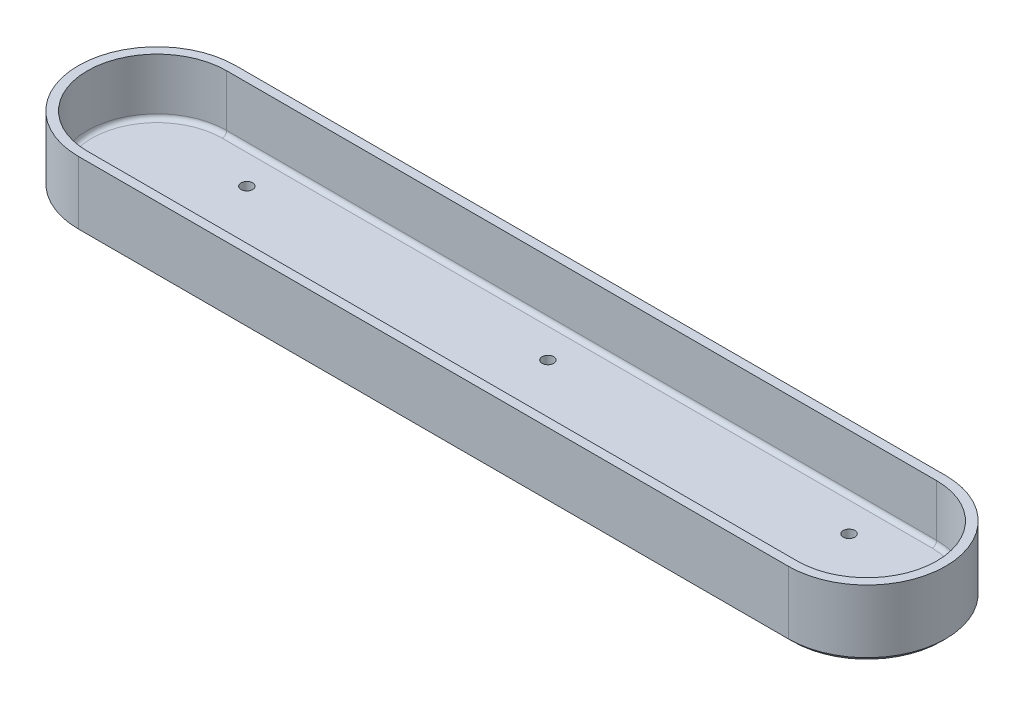
SolidWorks part; units mm, degrees
material "PLA"
ref_plane "Front Plane" through (0, 0, 0) normal (0, 0, 1) x (1, 0, 0)
ref_plane "Top Plane" through (0, 0, 0) normal (0, 1, 0) x (1, 0, 0)
ref_plane "Right Plane" through (0, 0, 0) normal (1, 0, 0) x (0, 0, -1)
sketch "Sketch1" plane through (0, 0, 0) normal (0, 1, 0) x (1, 0, 0)
  line L0 (-100.33, 0) -> (100.33, 0) construction
  line L1 (0, -55.9739) -> (0, 55.9739) construction
  line L2 (-100.33, 19.685) -> (100.33, 19.685)
  line L3 (-100.33, -19.685) -> (100.33, -19.685)
  arc A0 (-100.33, 19.685) -> (-100.33, -19.685) centre (-100.33, 0) ccw
  arc A1 (100.33, 19.685) -> (100.33, -19.685) centre (100.33, 0) cw
  circle A2 centre (-100.33, 0) radius 19.05 construction
  point P4 (0, 0)
  point P10 (0, 0)
  dimension "D2" = 0.635
  dimension "D3" = 38.1
  dimension "D1" = 200.66
extrude "MainBlock" add sketch "Sketch1" along normal blind 3.175
sketch "Sketch2" plane through (0, 0, 0) normal (0, -1, 0) x (1, 0, 0)
  line L0 (0, 0) -> (0, 50000) construction
  line L1 (-100.33, 22.225) -> (100.33, 22.225)
  line L2 (-100.33, -19.685) -> (100.33, -19.685)
  line L3 (100.33, 19.685) -> (-100.33, 19.685)
  line L5 (100.33, 19.685) -> (-100.33, 19.685)
  line L6 (-95.25, 0) -> (49904.75, 0) construction
  line L7 (100.33, -19.685) -> (-100.33, -19.685)
  line L8 (-100.33, -22.225) -> (100.33, -22.225)
  arc A0 (-100.33, 22.225) -> (-100.33, -22.225) centre (-100.33, 0) ccw
  arc A1 (100.33, 19.685) -> (100.33, -19.685) centre (100.33, 0) cw
  arc A2 (-100.33, 19.685) -> (-100.33, -19.685) centre (-100.33, 0) ccw
  arc A3 (100.33, -19.685) -> (100.33, 19.685) centre (100.33, 0) ccw
  arc A4 (-100.33, 19.685) -> (-100.33, -19.685) centre (-100.33, 0) ccw
  arc A6 (100.33, 22.225) -> (100.33, -22.225) centre (100.33, 0) cw
  point P0 (0, 19.685)
  point P15 (0, 22.225)
  point P16 (0, -19.685)
  point P19 (0, -22.225)
  dimension "D2" = 2.54
  dimension "2.1" = 44.45
  dimension "D1" = 0
extrude "Boss-Extrude1" add sketch "Sketch2" against normal blind 19.05
sketch "Sketch3" plane through (0, 0, 0) normal (0, -1, 0) x (1, 0, 0)
  line L0 (0, 0) -> (50000, 0) construction
  line L1 (0, 0) -> (0, 50000) construction
  line L2 (-100.33, 0.9216) -> (-100.33, 50000.9216) construction
  arc A0 (-100.33, 22.225) -> (-100.33, -22.225) centre (-100.33, 0) ccw construction
  arc A1 (-100.33, 22.225) -> (-100.33, -22.225) centre (-100.33, 0) ccw construction
  circle A2 centre (0, 10.16) radius 1.651
  circle A3 centre (-85.09, 10.16) radius 1.651
  circle A4 centre (85.09, 10.16) radius 1.651
  circle A5 centre (85.09, -10.16) radius 1.651
  circle A6 centre (-85.09, -10.16) radius 1.651
  circle A7 centre (0, -10.16) radius 1.651
  dimension "D1" = 3.302
  dimension "D4" = 3.302
  dimension "D2" = 10.16
  dimension "D3" = 10.16
  dimension "D5" = 15.24
extrude "Mount-Holes" cut sketch "Sketch3" against normal through all
fillet "Fillet1" radius 1.27 4 edges at (120.015, 3.175, 0) (0, 3.175, 19.685) (-120.015, 3.175, 0) (0, 3.175, -19.685)
chamfer "Chamfer1" distance 1.27 angle 45 4 edges at (0, 0, 22.225) (-122.555, 0, 0) (122.555, 0, 0) (0, 0, -22.225)
equation "\"D4@Sketch3\"=\"D1@Sketch3\""
